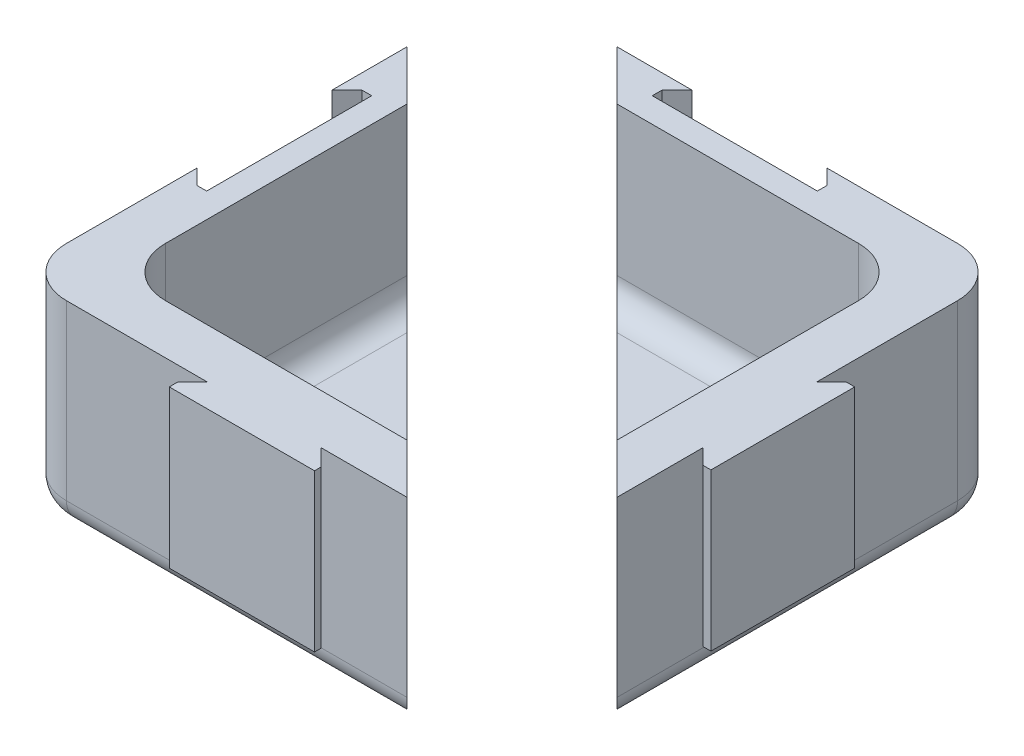
SolidWorks part; units mm, degrees
ref_plane "Front Plane" through (0, 0, 0) normal (0, 0, 1) x (1, 0, 0)
ref_plane "Top Plane" through (0, 0, 0) normal (0, 1, 0) x (1, 0, 0)
ref_plane "Right Plane" through (0, 0, 0) normal (1, 0, 0) x (0, 0, -1)
sketch "Sketch1" plane through (0, 0, 0) normal (0, 1, 0) x (1, 0, 0)
  line L1 (-50, 50) -> (50, 50)
  line L2 (-50, 50) -> (-50, -50)
  line L3 (-50, -50) -> (50, -50)
  line L4 (50, 50) -> (50, -50)
  line L5 (-50, 50) -> (50, -50) construction
  line L6 (-50, -50) -> (50, 50) construction
  point P0 (0, 0)
  dimension "D1" = 100
  dimension "D2" = 100
extrude "Boss-Extrude1" add sketch "Sketch1" along normal blind 40
shell "Shell1" thickness 10
sketch "Sketch2" plane through (0, 40, 0) normal (0, 1, 0) x (1, 0, 0)
  line L0 (-50, 45) -> (-16.6667, 45) construction
  line L1 (-50, 50) -> (-50, -50) construction
  line L2 (50, -50) -> (50, 50) construction
  line L3 (40, 40) -> (-40, 40) construction
  line L4 (-13.6667, 50) -> (-16.6667, 47)
  line L5 (50, 50) -> (-50, 50) construction
  line L6 (-16.6667, 45) -> (16.6667, 45)
  line L7 (16.6667, 47) -> (13.6667, 50)
  line L8 (-13.6667, 50) -> (13.6667, 50)
  line L9 (-16.6667, 47) -> (-16.6667, 45)
  line L10 (16.6667, 47) -> (16.6667, 45)
  line L11 (-16.6667, 45) -> (16.6667, 45) construction
  line L12 (16.6667, 45) -> (50, 45) construction
  point P9 (0, 0)
  point P13 (0, 45)
  point P14 (0, 0)
  point P19 (-14.9065, 45)
  dimension "D3" = 100
  dimension "D4" = 33.3333
  dimension "D1" = 5
  dimension "D2" = 45
  dimension "D5" = 2
  dimension "D6" = 2
extrude "Cut-Extrude1" cut sketch "Sketch2" against normal blind 32
sketch "Sketch3" plane through (0, 40, 0) normal (0, 1, 0) x (1, 0, 0)
  line L0 (-11.6667, -50) -> (-16.6667, -55) construction
  line L1 (-50, -50) -> (50, -50) construction
  line L2 (-16.6667, -55) -> (16.6667, -55) construction
  line L3 (16.6667, -55) -> (11.6667, -50) construction
  line L4 (11.6667, -50) -> (-11.6667, -50) construction
  line L5 (-50, -45) -> (50, -45) construction
  line L6 (-50, 50) -> (-50, -50) construction
  line L7 (50, -50) -> (50, 50) construction
  line L8 (-40, -40) -> (40, -40) construction
  line L9 (-11.4545, -50) -> (-14.5167, -53.0621)
  line L10 (-11.4545, -50) -> (11.4545, -50)
  line L11 (-14.5167, -54.7) -> (14.8167, -54.7)
  line L12 (-11.5606, -50.1061) -> (-16.5606, -55.1061) construction
  line L13 (14.6667, -53) -> (14.6667, -55) construction
  line L14 (14.8167, -53.3621) -> (11.4545, -50)
  line L15 (-14.6667, -53) -> (-14.6667, -55) construction
  line L16 (-14.5167, -53.0621) -> (-14.5167, -54.7)
  line L18 (-14.5167, -53) -> (-14.5167, -55) construction
  line L20 (14.8167, -53.3621) -> (14.8167, -54.7)
  point P4 (0, -50)
  dimension "D1" = 45
  dimension "D2" = 5
  dimension "D3" = 100
  dimension "D4" = 33.3333
  dimension "D5" = 5
  dimension "D7" = 0.3
  dimension "D8" = 0.15
  dimension "D9" = 2
  dimension "D10" = 2
  dimension "D12" = 0.15
  dimension "D6" = 0.15
  dimension "D11" = 0.15
extrude "Boss-Extrude2" add sketch "Sketch3" against normal blind 31.7
sketch "Sketch4" plane through (0, 40, 0) normal (0, 1, 0) x (1, 0, 0)
  line L4 (-45, 16.6667) -> (-45, -16.6667)
  line L5 (-47, -16.6667) -> (-50, -13.6667)
  line L6 (-50, 50) -> (-50, -50) construction
  line L7 (-50, -13.6667) -> (-50, 13.6667)
  line L8 (-50, 13.6667) -> (-47, 16.6667)
  line L9 (-47, 16.6667) -> (-45, 16.6667)
  line L10 (-47, -16.6667) -> (-45, -16.6667)
  line L11 (-45, 16.6667) -> (-45, -16.6667) construction
  point P0 (-45, 0)
  dimension "D2" = 45
  dimension "D3" = 5
  dimension "D5" = 2
  dimension "D4" = 2
  dimension "D1" = 33.3333
extrude "Cut-Extrude2" cut sketch "Sketch4" against normal blind 32
sketch "Sketch5" plane through (0, 40, 0) normal (0, 1, 0) x (1, 0, 0)
  line L0 (50, 11.6667) -> (50, -11.6667) construction
  line L1 (50, -50) -> (50, 50) construction
  line L2 (50, -11.6667) -> (55, -16.6667) construction
  line L3 (55, -16.6667) -> (55, 16.6667) construction
  line L4 (55, 16.6667) -> (50, 11.6667) construction
  line L5 (45, 50) -> (45, -50) construction
  line L6 (50, 50) -> (13.6667, 50) construction
  line L7 (11.4545, -50) -> (50, -50) construction
  line L8 (50, 11.4545) -> (50, -11.4545)
  line L9 (40, -40) -> (40, 40) construction
  line L10 (50, -11.4545) -> (53.0621, -14.5167)
  line L11 (53, 14.6667) -> (55, 14.6667) construction
  line L12 (54.7, -14.5167) -> (54.7, 14.5167)
  line L13 (54.7, -16.6667) -> (54.7, 16.6667) construction
  line L14 (53.0621, 14.5167) -> (50, 11.4545)
  line L15 (50.1061, -11.5606) -> (55.1061, -16.5606) construction
  line L16 (55, -14.6667) -> (53, -14.6667) construction
  line L17 (53.0621, 14.5167) -> (54.7, 14.5167)
  line L18 (54.7, -14.5167) -> (53.0621, -14.5167)
  line L19 (55, -14.5167) -> (53, -14.5167) construction
  line L20 (53, 14.5167) -> (55, 14.5167) construction
  point P14 (50, 0)
  dimension "D4" = 33.3333
  dimension "D9" = 2
  dimension "D1" = 5
  dimension "D2" = 45
  dimension "D3" = 5
  dimension "D7" = 0.15
  dimension "D8" = 2
  dimension "D5" = 0.15
  dimension "D6" = 0.3
  dimension "D10" = 0.15
extrude "Boss-Extrude3" add sketch "Sketch5" against normal up to surface (31.7 mm away) up to face at (0.1, 8.3, 52.6374)
fillet "Fillet1" radius 10 8 edges at (40, 22.5, 40) (50, 20, 50) (50, 20, -50) (40, 22.5, -40) (-40, 22.5, -40) (-50, 20, -50) (-40, 22.5, 40) (-50, 20, 50)
fillet "Fillet2" radius 5 16 edges at (-47.0711, 0, -47.0711) (-50, 0, 0) (-47.0711, 0, 47.0711) (0, 0, 50) (47.0711, 0, 47.0711) (50, 0, 0) (47.0711, 0, -47.0711) (0, 0, -50) (37.0711, 5, 37.0711) (0, 5, 40) (-37.0711, 5, 37.0711) (-40, 5, 0) (-37.0711, 5, -37.0711) (0, 5, -40) (37.0711, 5, -37.0711) (40, 5, 0)
sketch "Sketch7" plane through (0, 40, 0) normal (0, 1, 0) x (1, 0, 0)
  line L0 (-47.0711, 47.0711) -> (47.0711, -47.0711)
  arc A0 (-40, 50) -> (-50, 40) centre (-40, 40) ccw construction
  arc A1 (40, -50) -> (50, -40) centre (40, -40) ccw construction
extrude "Cut-Extrude-Thin1" cut sketch "Sketch7" against normal through all both and the other way through all thin thin type mid plane wall 30
equation "\"x\"= 100"
equation "\"y\"= 100"
equation "\"h\" = 40"
equation "\"D1@Sketch1\"=\"x\""
equation "\"D2@Sketch1\"=\"y\""
equation "\"D1@Cut-Extrude1\"=\"h\"*0.8"
equation "\"D5@Sketch3\"=\"D2@Sketch3\""
equation "\"Tolerance\"= 0.15"
equation "\"D6@Sketch3\"=\"Tolerance\""
equation "\"D7@Sketch3\"=\"Tolerance\"*2"
equation "\"D8@Sketch3\"=\"Tolerance\""
equation "\"D1@Boss-Extrude2\"=\"h\"*0.8 - (\"Tolerance\" * 2)"
equation "\"D4@Sketch3\"=\"x\"/3"
equation "\"D1@Cut-Extrude2\"=\"h\"*0.8"
equation "\"D3@Sketch5\"=\"D1@Sketch5\""
equation "\"D4@Sketch5\"=\"y\"/3"
equation "\"D6@Sketch5\"=\"Tolerance\"*2"
equation "\"D5@Sketch5\"=\"Tolerance\""
equation "\"D7@Sketch5\"=\"Tolerance\""
equation "\"D1@Boss-Extrude1\"=\"h\""
equation "\"D6@Sketch2\"=\"D5@Sketch2\""
equation "\"Flat\"= 2"
equation "\"D5@Sketch2\"=\"Flat\""
equation "\"D4@Sketch2\"=\"x\"/3"
equation "\"D4@Sketch4\"=\"Flat\""
equation "\"D5@Sketch4\"=\"D4@Sketch4\""
equation "\"D1@Sketch4\"=\"y\"/3"
equation "\"D3@Sketch4\"=5"
equation "\"D9@Sketch3\"=\"Flat\""
equation "\"D10@Sketch3\"=\"D9@Sketch3\""
equation "\"D11@Sketch3\"=\"Tolerance\""
equation "\"D12@Sketch3\"=\"Tolerance\""
equation "\"D8@Sketch5\"=\"Flat\""
equation "\"D9@Sketch5\"=\"D8@Sketch5\""
equation "\"D10@Sketch5\"=\"Tolerance\""
